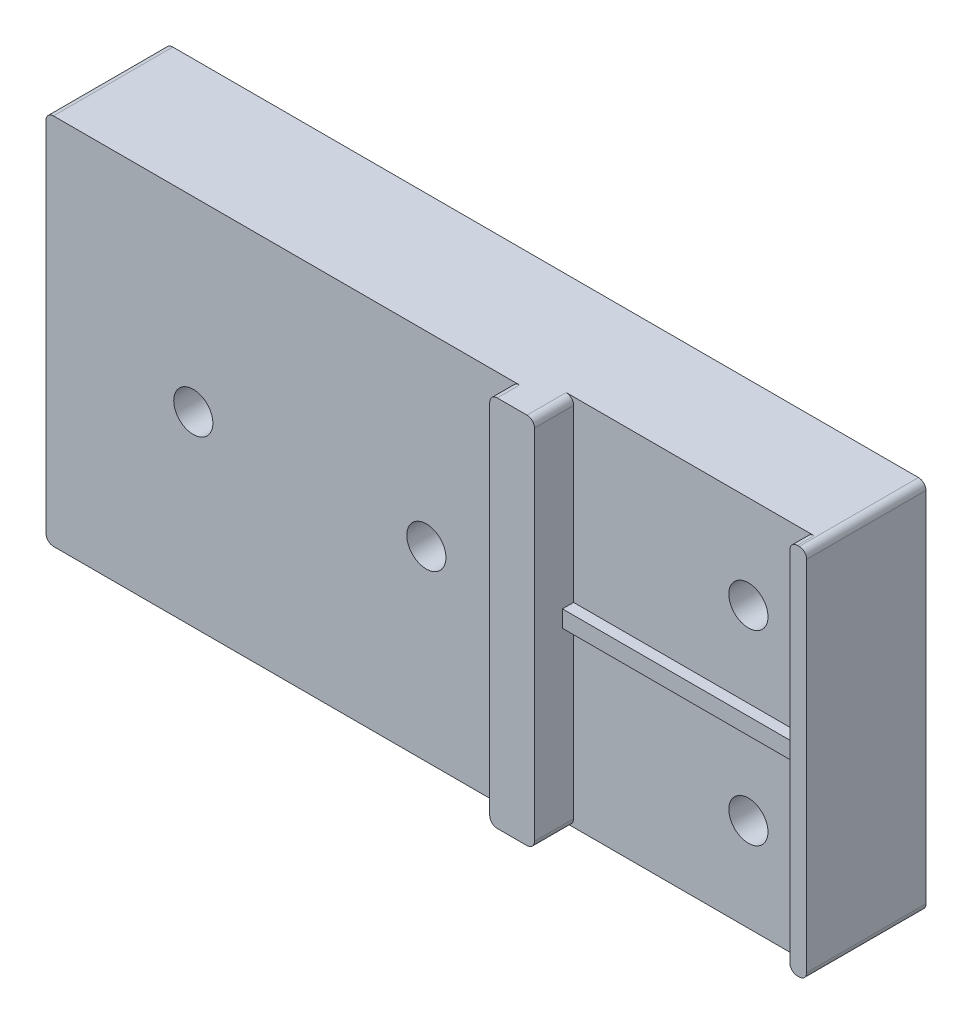
SolidWorks part; units mm, degrees
ref_plane "Front Plane" through (0, 0, 0) normal (0, 0, 1) x (1, 0, 0)
ref_plane "Top Plane" through (0, 0, 0) normal (0, 1, 0) x (1, 0, 0)
ref_plane "Right Plane" through (0, 0, 0) normal (1, 0, 0) x (0, 0, -1)
sketch "Sketch1" plane through (0, 0, 0) normal (0, -1, 0) x (1, 0, 0)
  line L19 (14, 12.8) -> (40.8, 12.8) construction
  line L20 (14, 15.2) -> (14, 12.8)
  line L21 (-40.8, 0) -> (-40.8, 12.8)
  line L22 (40.8, 0) -> (-40.8, 0)
  line L23 (40.8, 12.8) -> (40.8, 0)
  line L24 (9.2, 15.2) -> (14, 15.2)
  line L25 (9.2, 12.8) -> (9.2, 15.2)
  line L26 (-40.8, 12.8) -> (9.2, 12.8)
  line L32 (-40.8, 12.8) -> (-40.8, 31) construction
  line L33 (-40.8, 31) -> (-40.8, 43.8) construction
  line L34 (-40.8, 43.8) -> (40.8, 43.8) construction
  line L35 (40.8, 43.8) -> (40.8, 31) construction
  line L36 (14, 12.8) -> (14, 11)
  line L37 (14, 11) -> (39, 11)
  line L38 (39, 11) -> (39, 12.8)
  line L39 (39, 12.8) -> (40.8, 12.8)
  line L40 (40.8, 31) -> (39, 31) construction
  line L41 (39, 31) -> (39, 32.8) construction
  line L42 (39, 32.8) -> (14, 32.8) construction
  line L43 (14, 32.8) -> (14, 31) construction
  line L44 (14, 28.6) -> (9.2, 28.6) construction
  line L45 (9.2, 31) -> (-40.8, 31) construction
  line L46 (14, 31) -> (14, 28.6) construction
  line L47 (9.2, 31) -> (9.2, 28.6) construction
  line L48 (-45.1978, 21.9) -> (59.4667, 21.9) construction
  line L49 (51.1238, 39.4) -> (51.1238, 4.4) construction
  point P0 (0, 0)
  point P2 (-40.8, 21.9)
  point P29 (51.1238, 21.9)
  dimension "D2" = 12.8
  dimension "D3" = 50
  dimension "D4" = 4.8
  dimension "D6" = 2.4
  dimension "D7" = 18.2
  dimension "D8" = 21.8
  dimension "D9" = 1.8
  dimension "D10" = 25
  dimension "D11" = 1.8
  dimension "D12" = 11
  dimension "D13" = 35
  dimension "D14" = 6.6
  dimension "D15" = 4.4
extrude "Boss-Extrude1" add sketch "Sketch1" along normal blind 40
sketch "Sketch6" plane through (0, 0, 0) normal (0, 0, -1) x (-1, 0, 0)
  line L0 (40.8, -40) -> (40.8, 0) construction
  line L1 (-9.2, -40) -> (-9.2, 0) construction
  line L2 (-9.2, -40) -> (-9.2, 0) construction
  circle A0 centre (25, -20) radius 2.1
  circle A1 centre (0, -20) radius 2.1
  point P4 (40.8, -20)
  dimension "D1" = 4.2
  dimension "D3" = 4.2
  dimension "D2" = 34.2
  dimension "D4" = 9.2
extrude "Cut-Extrude4" cut sketch "Sketch6" against normal up to surface (12.8 mm away) up to face at (-15.8, -20, 12.8)
sketch "Sketch10" plane through (0, 0, 11) normal (0, 0, 1) x (1, 0, 0)
  line L0 (14, -20) -> (39, -20) construction
  line L1 (39, -20) -> (39, 0) construction
  line L2 (39, 0) -> (26.5, -20) construction
  line L3 (26.5, -20) -> (39, -40) construction
  line L4 (39, 0) -> (14, 0)
  line L5 (14, 0) -> (14, -40)
  line L6 (14, -40) -> (39, -40)
  line L7 (39, -40) -> (39, 0)
  line L8 (39, 0) -> (14, 0) construction
  line L9 (14, 0) -> (14, -40) construction
  line L10 (14, -40) -> (39, -40) construction
  line L11 (39, -40) -> (39, 0) construction
  circle A0 centre (32.75, -10) radius 2.1
  circle A1 centre (32.75, -30) radius 2.1
  dimension "D2" = 4.2
  dimension "D1" = 0
extrude "Cut-Extrude7" cut sketch "Sketch10" against normal up to next
sketch "Sketch11" plane through (0, 0, 0) normal (0, 0, -1) x (-1, 0, 0)
  circle A4 centre (-32.75, -10) radius 4.75
  circle A5 centre (-32.75, -30) radius 4.75
  dimension "D1" = 9.5
extrude "Cut-Extrude8" cut sketch "Sketch11" against normal blind 4.5
sketch "Sketch12" plane through (0, 0, 4.5) normal (0, 0, -1) x (-1, 0, 0)
  circle A0 centre (-32.75, -10) radius 2.1 construction
  circle A1 centre (-32.75, -30) radius 2.1 construction
  circle A2 centre (-32.75, -10) radius 2.1
  circle A3 centre (-32.75, -30) radius 2.1
extrude "Boss-Extrude2" add sketch "Sketch12" against normal blind 0.6
sketch "Sketch13" plane through (0, 0, 11) normal (0, 0, 1) x (1, 0, 0)
  line L0 (39, -40) -> (39, 0) construction
  line L1 (14, -19.1) -> (39, -19.1)
  line L2 (14, -19.1) -> (14, -20.9)
  line L3 (14, -20.9) -> (39, -20.9)
  line L4 (39, -19.1) -> (39, -20.9)
  line L5 (14, -19.1) -> (39, -20.9) construction
  line L6 (14, -20.9) -> (39, -19.1) construction
  line L7 (14, -40) -> (14, 0) construction
  line L8 (39, -40) -> (39, 0) construction
  line L9 (14, -40) -> (14, 0) construction
  point P0 (26.5, -20)
  point P9 (14, -20)
  point P10 (14, -20)
  point P11 (39, -20)
  point P12 (39, -20)
  dimension "D1" = 1.8
extrude "Boss-Extrude3" add sketch "Sketch13" along normal blind 1.2
fillet "Fillet1" radius 0.8 10 edges at (39, 0, 11.9) (39, -40, 11.9) (14, -40, 13.1) (9.2, -40, 14) (9.2, 0, 14) (14, 0, 13.1) (-40.8, 0, 6.4) (-40.8, -40, 6.4) (40.8, 0, 6.4) (40.8, -40, 6.4)
sketch "Sketch14" plane through (0, 0, 0) normal (0, 0, -1) x (-1, 0, 0)
  line L0 (2.1, -40) -> (2.1, 0) construction
  line L1 (40, -40) -> (-40, -40) construction
  line L2 (40, 0) -> (-40, 0) construction
  line L3 (27.1, -40) -> (27.1, 0) construction
  circle A3 centre (25, -20) radius 2.1 construction
  circle A4 centre (0, -20) radius 2.1 construction
  text T0 "      9           mm" font "Century Gothic" height 3.5
  text T1 "     34          mm" font "Century Gothic" height 3.5
extrude "Cut-Extrude9" cut sketch "Sketch14" against normal blind 1.2
